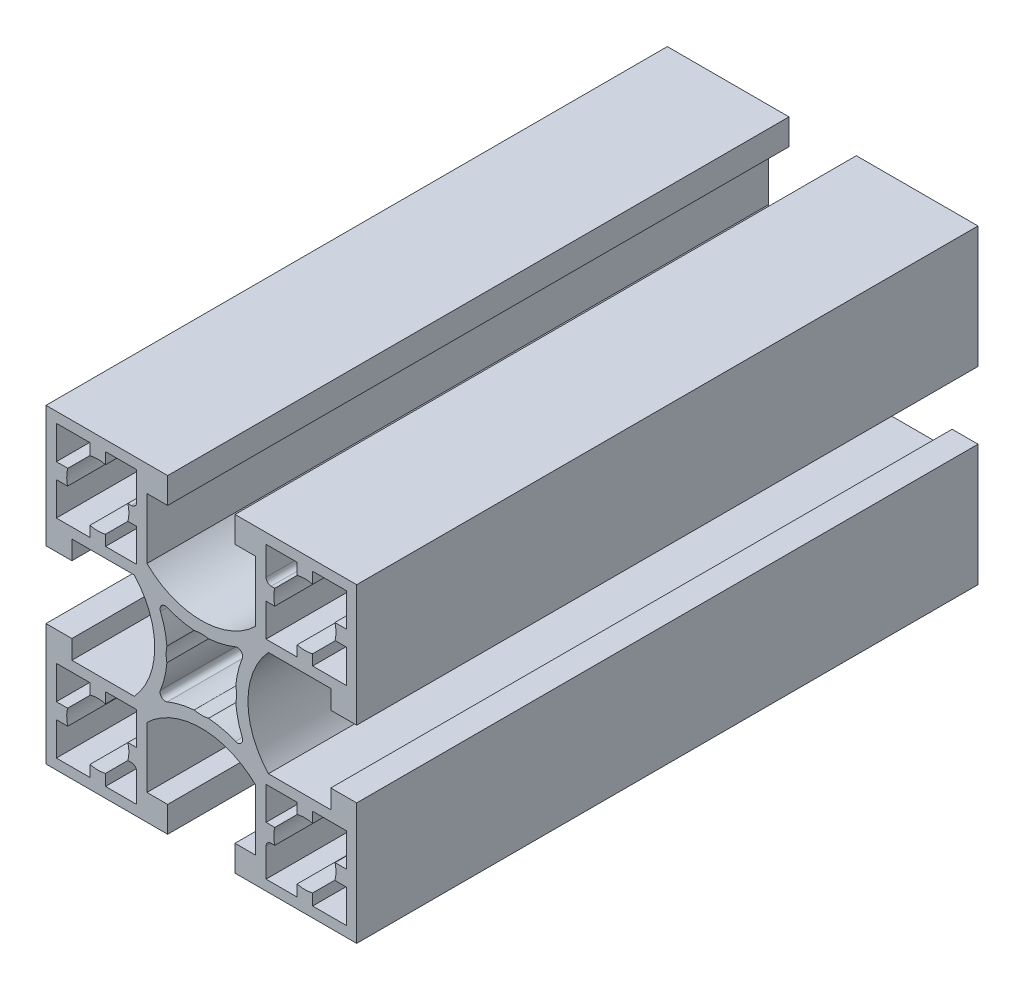
SolidWorks part; units mm, degrees
material "A6061-T6"
ref_plane "前基準面" through (0, 0, 0) normal (0, 0, 1) x (1, 0, 0)
ref_plane "上基準面" through (0, 0, 0) normal (0, 1, 0) x (1, 0, 0)
ref_plane "右基準面" through (0, 0, 0) normal (1, 0, 0) x (0, 0, -1)
ref_plane "平面1"
sketch "草圖1" plane through (0, 0, 0) normal (0, 0, 1) x (1, 0, 0)
  line L0 (-15, -3.25) -> (-12.5, -3.25)
  line L1 (-12.5, -3.25) -> (-12.5, -5.0724)
  line L2 (-12.5, -5.0724) -> (-6.4755, -5.0724)
  line L3 (-6.4755, 5.0724) -> (-12.5, 5.0724)
  line L4 (-12.5, 5.0724) -> (-12.5, 3.25)
  line L5 (-12.5, 3.25) -> (-15, 3.25)
  line L6 (-15, 3.25) -> (-15, 15)
  line L7 (-15, 15) -> (-3.25, 15)
  line L8 (-3.25, 15) -> (-3.25, 12.5)
  line L9 (-3.25, 12.5) -> (-5.25, 12.5)
  line L10 (-5.25, 12.5) -> (-5.25, 6.6439)
  line L11 (5.25, 6.6439) -> (5.25, 12.5)
  line L12 (5.25, 12.5) -> (3.25, 12.5)
  line L13 (3.25, 12.5) -> (3.25, 15)
  line L14 (3.25, 15) -> (15, 15)
  line L15 (15, 15) -> (15, 3.25)
  line L16 (15, 3.25) -> (12.5, 3.25)
  line L17 (12.5, 3.25) -> (12.5, 5.0724)
  line L18 (12.5, 5.0724) -> (6.4755, 5.0724)
  line L19 (6.4755, -5.0724) -> (12.5, -5.0724)
  line L20 (12.5, -5.0724) -> (12.5, -3.25)
  line L21 (12.5, -3.25) -> (15, -3.25)
  line L22 (15, -3.25) -> (15, -15)
  line L23 (15, -15) -> (3.25, -15)
  line L24 (3.25, -15) -> (3.25, -12.5)
  line L25 (3.25, -12.5) -> (5.25, -12.5)
  line L26 (5.25, -12.5) -> (5.25, -6.6439)
  line L27 (-5.25, -6.6439) -> (-5.25, -12.5)
  line L28 (-5.25, -12.5) -> (-3.25, -12.5)
  line L29 (-3.25, -12.5) -> (-3.25, -15)
  line L30 (-3.25, -15) -> (-15, -15)
  line L31 (-15, -15) -> (-15, -3.25)
  line L32 (-9.25, -6.0724) -> (-6.25, -6.0724)
  line L33 (-6.25, -6.0724) -> (-6.25, -9.25)
  line L34 (-6.25, -9.25) -> (-7.0953, -9.25)
  line L35 (-7.0953, -10.75) -> (-6.75, -10.75)
  line L36 (-6.25, -11.25) -> (-6.25, -14)
  line L37 (-6.25, -14) -> (-9.25, -14)
  line L38 (-9.25, -14) -> (-9.25, -12.9047)
  line L39 (-10.75, -12.9047) -> (-10.75, -14)
  line L40 (-10.75, -14) -> (-14, -14)
  line L41 (-14, -14) -> (-14, -10.7862)
  line L42 (-14, -10.7862) -> (-12.8951, -10.7862)
  line L43 (-12.9138, -9.2862) -> (-14, -9.2862)
  line L44 (-14, -9.2862) -> (-14, -6.0724)
  line L45 (-14, -6.0724) -> (-10.75, -6.0724)
  line L46 (-10.75, -6.0724) -> (-10.75, -7.0953)
  line L47 (-9.25, -7.0953) -> (-9.25, -6.0724)
  line L48 (-14, 6.0724) -> (-10.75, 6.0724)
  line L49 (-10.75, 6.0724) -> (-10.75, 7.0953)
  line L50 (-9.25, 7.0953) -> (-9.25, 6.0724)
  line L51 (-9.25, 6.0724) -> (-6.25, 6.0724)
  line L52 (-6.25, 6.0724) -> (-6.25, 9.25)
  line L53 (-6.25, 9.25) -> (-7.0953, 9.25)
  line L54 (-7.0953, 10.75) -> (-6.75, 10.75)
  line L55 (-6.25, 11.25) -> (-6.25, 14)
  line L56 (-6.25, 14) -> (-9.25, 14)
  line L57 (-9.25, 14) -> (-9.25, 12.9047)
  line L58 (-10.75, 12.9047) -> (-10.75, 14)
  line L59 (-10.75, 14) -> (-14, 14)
  line L60 (-14, 14) -> (-14, 10.7862)
  line L61 (-14, 10.7862) -> (-12.8951, 10.7862)
  line L62 (-12.9138, 9.2862) -> (-14, 9.2862)
  line L63 (-14, 9.2862) -> (-14, 6.0724)
  line L64 (14, 14) -> (14, 10.7862)
  line L65 (14, 10.7862) -> (12.8951, 10.7862)
  line L66 (12.9138, 9.2862) -> (14, 9.2862)
  line L67 (14, 9.2862) -> (14, 6.0724)
  line L68 (14, 6.0724) -> (10.75, 6.0724)
  line L69 (10.75, 6.0724) -> (10.75, 7.0953)
  line L70 (9.25, 7.0953) -> (9.25, 6.0724)
  line L71 (9.25, 6.0724) -> (6.25, 6.0724)
  line L72 (6.25, 6.0724) -> (6.25, 9.25)
  line L73 (6.25, 9.25) -> (7.0953, 9.25)
  line L74 (7.0953, 10.75) -> (6.75, 10.75)
  line L75 (6.25, 11.25) -> (6.25, 14)
  line L76 (6.25, 14) -> (9.25, 14)
  line L77 (9.25, 14) -> (9.25, 12.9047)
  line L78 (10.75, 12.9047) -> (10.75, 14)
  line L79 (10.75, 14) -> (14, 14)
  line L80 (7.0953, -10.75) -> (6.75, -10.75)
  line L81 (6.25, -11.25) -> (6.25, -14)
  line L82 (6.25, -14) -> (9.25, -14)
  line L83 (9.25, -14) -> (9.25, -12.9047)
  line L84 (10.75, -12.9047) -> (10.75, -14)
  line L85 (10.75, -14) -> (14, -14)
  line L86 (14, -14) -> (14, -10.7862)
  line L87 (14, -10.7862) -> (12.8951, -10.7862)
  line L88 (12.9138, -9.2862) -> (14, -9.2862)
  line L89 (14, -9.2862) -> (14, -6.0724)
  line L90 (14, -6.0724) -> (10.75, -6.0724)
  line L91 (10.75, -6.0724) -> (10.75, -7.0953)
  line L92 (9.25, -7.0953) -> (9.25, -6.0724)
  line L93 (9.25, -6.0724) -> (6.25, -6.0724)
  line L94 (6.25, -6.0724) -> (6.25, -9.25)
  line L95 (6.25, -9.25) -> (7.0953, -9.25)
  arc A0 (-6.4755, -5.0724) -> (-6.4755, 5.0724) centre (-12, 0) ccw
  arc A1 (-5.25, 6.6439) -> (5.25, 6.6439) centre (0, 12) ccw
  arc A2 (6.4755, 5.0724) -> (6.4755, -5.0724) centre (12, 0) ccw
  arc A3 (5.25, -6.6439) -> (-5.25, -6.6439) centre (0, -12) ccw
  arc A4 (3.9488, 3.2966) -> (3.3279, 0.6964) centre (12, 0) ccw
  arc A5 (3.3279, -0.6964) -> (3.3279, 0.6964) centre (0, 0) ccw
  arc A6 (3.3279, -0.6964) -> (3.9488, -3.2966) centre (12, 0) ccw
  arc A7 (3.2966, -3.9488) -> (3.9488, -3.2966) centre (3.486, -3.486) ccw
  arc A8 (3.2966, -3.9488) -> (0.6964, -3.3279) centre (0, -12) ccw
  arc A9 (-0.6964, -3.3279) -> (0.6964, -3.3279) centre (0, 0) ccw
  arc A10 (-0.6964, -3.3279) -> (-3.2966, -3.9488) centre (0, -12) ccw
  arc A11 (-3.9488, -3.2966) -> (-3.2966, -3.9488) centre (-3.486, -3.486) ccw
  arc A12 (-3.9488, -3.2966) -> (-3.3279, -0.6964) centre (-12, 0) ccw
  arc A13 (-3.3279, 0.6964) -> (-3.3279, -0.6964) centre (0, 0) ccw
  arc A14 (-3.3279, 0.6964) -> (-3.9488, 3.2966) centre (-12, 0) ccw
  arc A15 (-3.2966, 3.9488) -> (-3.9488, 3.2966) centre (-3.486, 3.486) ccw
  arc A16 (-3.2966, 3.9488) -> (-0.6964, 3.3279) centre (0, 12) ccw
  arc A17 (0.6964, 3.3279) -> (-0.6964, 3.3279) centre (0, 0) ccw
  arc A18 (0.6964, 3.3279) -> (3.2966, 3.9488) centre (0, 12) ccw
  arc A19 (3.9488, 3.2966) -> (3.2966, 3.9488) centre (3.486, 3.486) ccw
  arc A20 (-7.0953, -10.75) -> (-7.0953, -9.25) centre (-10, -10) ccw
  arc A21 (-6.25, -11.25) -> (-6.75, -10.75) centre (-6.75, -11.25) ccw
  arc A22 (-10.75, -12.9047) -> (-9.25, -12.9047) centre (-10, -10) ccw
  arc A23 (-12.9138, -9.2862) -> (-12.8951, -10.7862) centre (-10, -10) ccw
  arc A24 (-9.25, -7.0953) -> (-10.75, -7.0953) centre (-10, -10) ccw
  arc A25 (-10.75, 7.0953) -> (-9.25, 7.0953) centre (-10, 10) ccw
  arc A26 (-7.0953, 9.25) -> (-7.0953, 10.75) centre (-10, 10) ccw
  arc A27 (-6.75, 10.75) -> (-6.25, 11.25) centre (-6.75, 11.25) ccw
  arc A28 (-9.25, 12.9047) -> (-10.75, 12.9047) centre (-10, 10) ccw
  arc A29 (-12.8951, 10.7862) -> (-12.9138, 9.2862) centre (-10, 10) ccw
  arc A30 (12.9138, 9.2862) -> (12.8951, 10.7862) centre (10, 10) ccw
  arc A31 (9.25, 7.0953) -> (10.75, 7.0953) centre (10, 10) ccw
  arc A32 (7.0953, 10.75) -> (7.0953, 9.25) centre (10, 10) ccw
  arc A33 (6.25, 11.25) -> (6.75, 10.75) centre (6.75, 11.25) ccw
  arc A34 (10.75, 12.9047) -> (9.25, 12.9047) centre (10, 10) ccw
  arc A35 (6.75, -10.75) -> (6.25, -11.25) centre (6.75, -11.25) ccw
  arc A36 (9.25, -12.9047) -> (10.75, -12.9047) centre (10, -10) ccw
  arc A37 (12.8951, -10.7862) -> (12.9138, -9.2862) centre (10, -10) ccw
  arc A38 (10.75, -7.0953) -> (9.25, -7.0953) centre (10, -10) ccw
  arc A39 (7.0953, -9.25) -> (7.0953, -10.75) centre (10, -10) ccw
extrude "擠出1" add sketch "草圖1" along normal mid plane 60 contours A3 L26 L25 L24 L23 L22 L21 L20 L19 A2 L18 L17 L16 L15 L14 L13 L12 L11 A1 L10 L9 L8 L7 L6 L5 L4 L3 A0 L2 L1 L0 L31 L30 L29 L28 L27 A39 L95 L94 L93 L92 A38 L91 L90 L89 L88 A37 L87 L86 L85
sketch "草圖2"
  dimension "D1" = 15
  dimension "D2" = 15
extrude "DUJ-UP1" [suppressed] sketch "草圖2" blind 12
sketch "草圖3"
  dimension "D1" = 15
  dimension "D2" = 15
extrude "DUJ-UP2" [suppressed] sketch "草圖3" blind 12
sketch "草圖4"
  dimension "D1" = 15
  dimension "D2" = 15
extrude "DUJ-DOWN1" [suppressed] sketch "草圖4" blind 12
sketch "草圖5"
  dimension "D1" = 15
  dimension "D2" = 15
extrude "DUJ-DOWN2" [suppressed] sketch "草圖5" blind 12
sketch "草圖6"
  dimension "D1" = 15
  dimension "D2" = 15
extrude "DUJ-UP3" [suppressed] sketch "草圖6" blind 12
sketch "草圖7"
  dimension "D1" = 15
  dimension "D2" = 15
extrude "DUJ-UP4" [suppressed] sketch "草圖7" blind 12
sketch "草圖8"
  dimension "D1" = 15
  dimension "D2" = 15
extrude "DUJ-DOWN3" [suppressed] sketch "草圖8" blind 12
sketch "草圖9"
  dimension "D1" = 15
  dimension "D2" = 15
extrude "DUJ-DOWN4" [suppressed] sketch "草圖9" blind 12
equation "\"L1\"= 15'孔距"
equation "\"D2@草圖2\"=\"L1\""
equation "\"D1\"= 15'孔徑"
equation "\"D1@草圖2\"=\"D1\""
equation "\"D1@草圖3\"=\"D1\""
equation "\"D2@草圖3\"=\"L1\""
equation "\"D2@草圖4\"=\"L1\""
equation "\"D1@草圖4\"=\"D1\""
equation "\"D2@草圖5\"=\"D1\""
equation "\"D1@草圖5\"=\"L1\""
equation "\"D1@草圖6\"=\"D1\""
equation "\"D2@草圖6\"=\"L1\""
equation "\"D1@草圖7\"=\"D1\""
equation "\"D2@草圖7\"=\"L1\""
equation "\"D1@草圖8\"=\"L1\""
equation "\"D2@草圖8\"=\"D1\""
equation "\"D1@草圖9\"=\"D1\""
equation "\"D2@草圖9\"=\"L1\""
